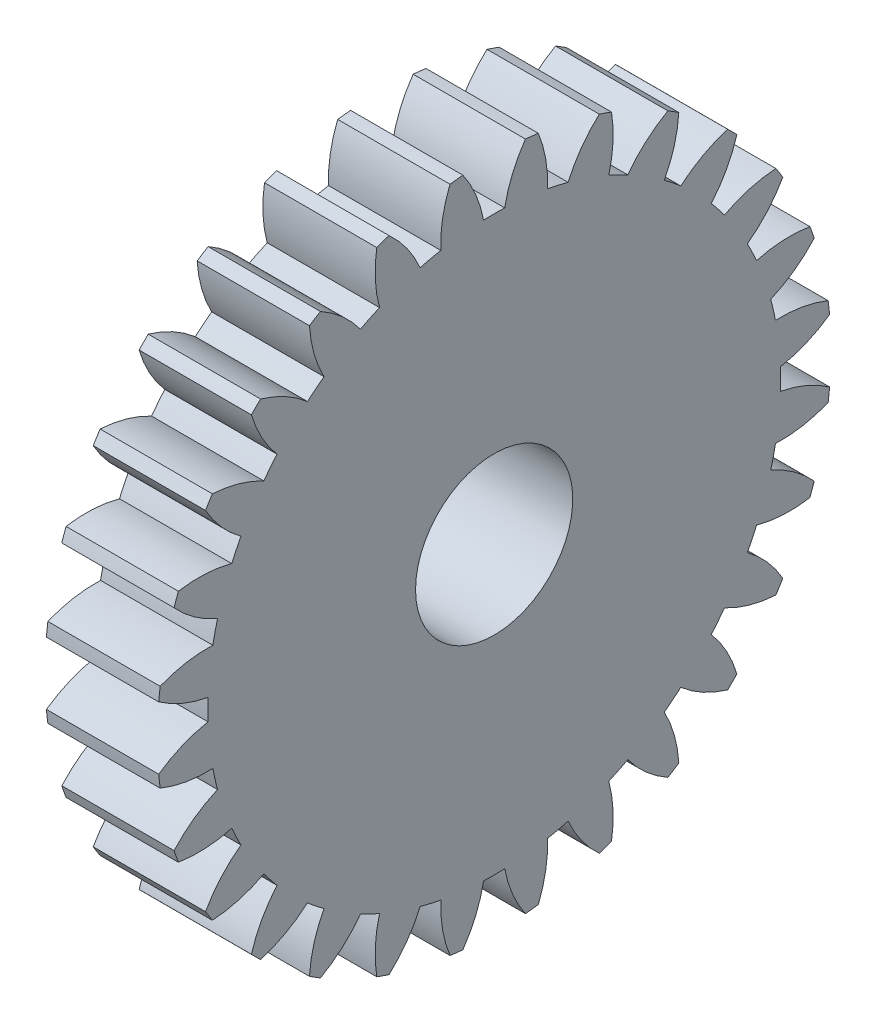
SolidWorks part; units mm, degrees
ref_plane "Plane1" through (0, 0, 0) normal (0, 0, 1) x (1, 0, 0)
ref_plane "Plane2" through (0, 0, 0) normal (0, 1, 0) x (1, 0, 0)
ref_plane "Plane3" through (0, 0, 0) normal (1, 0, 0) x (0, 0, -1)
sketch "HoldingSke" plane through (0, 0, 0) normal (0, 1, 0) x (1, 0, 0)
  line L0 (0, 0) -> (0.8829, -0.4695)
  line L1 (-15, 0) -> (100, 0) construction
  line L2 (0, 0) -> (-2.1039, 2.3779)
  line L3 (0, 0) -> (-11.863, 4.5341)
  line L4 (0, 0) -> (7.6251, 4.0544)
  line L5 (0, 0) -> (-46.8476, -17.4728)
  line L6 (0, 0) -> (-4.1448, -2.7965)
  line L7 (-2.1039, 2.3779) -> (8.6586, 51.2059)
  line L8 (-76.2, 54.61) -> (-75.2, 54.61)
  line L9 (-71.009, 38.7566) -> (-53.1078, 45.2721)
  line L10 (-76.2, 71.12) -> (104.1128, 71.12)
  line L11 (0, 0) -> (-5, 0)
  line L12 (-76.2, 101.6) -> (-76.162, 101.6)
  line L13 (24.9733, 27.94) -> (52.9518, 28.4284)
  line L14 (24.9733, 27.94) -> (24.9743, 27.94)
  line L15 (24.9733, 27.94) -> (100.4006, 29.5858)
  line L16 (-63.627, -1) -> (-12.827, -1)
  circle A0 centre (0, 0) radius 3.5
  circle A1 centre (0, 0) radius 12.749
  circle A2 centre (0, 0) radius 37.5
  circle A3 centre (0, 0) radius 3.5
  dimension "MHD" = 25.498
  dimension "Hub_dia" = 75
  dimension "Bore" = 7
  dimension "MBD" = 7
  dimension "Num_teeth" = 28
  dimension "Pitch" = 1
  dimension "Overall_len" = 50
  dimension "Show_teeth" = 28
  dimension "Thickness" = 5
  dimension "OAL" = 50.0001
  dimension "T_dim" = 1
  dimension "Ap" = 20
  dimension "H" = 19.05
  dimension "Pitch_radius" = 180.3128
  dimension "Width" = 5
  dimension "Backlash" = 0.038
  dimension "Addendum_fac" = 1
  dimension "Dedendum_fac" = 1.25
  dimension "Clearance_fac" = 0.25
  dimension "Dedendum_add" = 0.001
  dimension "Module" = 1
sketch "BasProSke" plane through (0, 0, 0) normal (0, 1, 0) x (1, 0, 0)
  line L0 (-10, 0) -> (60, 0) construction
  line L1 (0, 0) -> (0, 15)
  line L2 (0, 0) -> (5, 0)
  line L3 (5, 0) -> (5, 15)
  line L4 (5, 15) -> (0, 15)
  dimension "Thickness" = 5
  dimension "Diameter" = 30
revolve "Base-Revolve" add sketch "BasProSke" angle 360 about L0
sketch "TooCutSke" plane through (0, 0, 0) normal (1, 0, 0) x (0, 0, -1)
  line L1 (0, 0) -> (0, 107) construction
  line L2 (0, 0) -> (-0.8515, 13.9741) construction
  line L3 (0, 0) -> (-3.1309, 27.7873) construction
  line L4 (-0.8515, 13.9741) -> (-1.5654, 13.8936) construction
  arc A0 (0.4713, 12.7403) -> (-0.4713, 12.7403) centre (0, 0) ccw
  arc A1 (1.4098, 14.9591) -> (-1.4098, 14.9591) centre (0, 0) ccw
  circle A2 centre (0, 0) radius 14 construction
  circle A3 centre (0, 0) radius 13.1557 construction
  arc A4 (-0.4713, 12.7403) -> (-1.4098, 14.9591) centre (-5.9775, 11.7193) ccw
  arc A5 (1.4098, 14.9591) -> (0.4713, 12.7403) centre (5.9775, 11.7193) ccw
  dimension "Root_dia" = 25.498
  dimension "Overcut_dia" = 30.0508
  dimension "Pitch_dia" = 28
  dimension "Base_dia" = 26.3114
  dimension "Flank_rad" = 5.6
  dimension "Half_ang" = 6.429
  dimension "Half_CT" = 0.7185
extrude "ToothCut" cut sketch "TooCutSke" along normal through all
fillet "Breaks" [suppressed] radius 0.02
fillet "RootFillets" [suppressed] radius 0.251
pattern_circular "TeethCuts" count 28 every 12.857 about axis through (-10, 0, 0) along (1, 0, 0) of "ToothCut", "RootFillets", "Breaks"
sketch "HubNeaOneSke" plane through (0, 0, 0) normal (-1, 0, 0) x (0, 0, 1)
  circle A0 centre (0, 0) radius 12.749
  dimension "Diameter" = 25.498
extrude "HubNearOne" [suppressed] add sketch "HubNeaOneSke" along normal blind 45.0001
sketch "HubNeaBotSke" plane through (0, 0, 0) normal (-1, 0, 0) x (0, 0, 1)
  circle A0 centre (0, 0) radius 12.749
  dimension "Diameter" = 25.498
extrude "HubNearBoth" [suppressed] add sketch "HubNeaBotSke" along normal blind 22.5
ref_plane "FarPln" through (5, 0, 0) normal (1, 0, 0) x (0, 0, -1)
sketch "HubFarSke" plane through (5, 0, 0) normal (1, 0, 0) x (0, 0, -1)
  circle A0 centre (0, 0) radius 12.749
  dimension "Diameter" = 25.498
extrude "HubFar" [suppressed] add sketch "HubFarSke" along normal blind 22.5
sketch "BorSke" plane through (0, 0, 0) normal (1, 0, 0) x (0, 0, -1)
  circle A0 centre (0, 0) radius 3.5
  dimension "Diameter" = 7
extrude "Bore" cut sketch "BorSke" along normal mid plane 100.0001
sketch "KeySke" plane through (0, 0, 0) normal (1, 0, 0) x (0, 0, -1)
  line L0 (-1, 0) -> (-1, 4.5)
  line L1 (-1, 4.5) -> (1, 4.5)
  line L2 (1, 4.5) -> (1, 0)
  line L3 (0, 0) -> (0, 34) construction
  line L4 (-1, 0) -> (1, 0)
  dimension "Offset" = 4.5
  dimension "Width" = 2
extrude "Keyway" [suppressed] cut sketch "KeySke" along normal mid plane 100.0001
pattern_circular "Keyway2" [suppressed] count 2 every 90 about axis through (-10, 0, 0) along (1, 0, 0)
equation "' \"Module@HoldingSke\" = 6.35"
equation "' \"Num_teeth@HoldingSke\" = 12"
equation "' \"Ap@HoldingSke\" =  20"
equation "' \"Ap@HoldingSke\" = 20"
equation "' \"Width@HoldingSke\" = 0.5 * 25.4"
equation "' \"Hub_dia@HoldingSke\"= 1 * 25.4"
equation "' \"Hub_dia@HoldingSke\" = 1 * 25.4"
equation "' \"Overall_len@HoldingSke\" = 1.0 * 25.4"
equation "' \"Bore@HoldingSke\" = 0.75 * 25.4"
equation "' \"T_dim@HoldingSke\" = 0.1 * 25.4"
equation "' \"Width@KeySke\" = 0.25 * 25.4"
equation "' \"Show_teeth@HoldingSke\" = 13"
equation "' \"Backlash@HoldingSke\" = 0.009 * 25.4"
equation "' \"Addendum_fac@HoldingSke\" = 1.0"
equation "' \"Dedendum_fac@HoldingSke\" = 1.25"
equation "' \"Dedendum_add@HoldingSke\" = 0.00005 * 25.4"
equation "' \"Clearance_fac@HoldingSke\" = 0.25"
equation "\"Pitch@HoldingSke\" = 1 / \"Module@HoldingSke\""
equation "\"Overcut_dia@TooCutSke\" = (\"Num_teeth@HoldingSke\" + 2 * \"Addendum_fac@HoldingSke\") / \"Pitch@HoldingSke\" + 0.002 * 25.4"
equation "\"Pitch_dia@TooCutSke\" = \"Num_teeth@HoldingSke\" / \"Pitch@HoldingSke\""
equation "\"Base_dia@TooCutSke\" = \"Num_teeth@HoldingSke\" / \"Pitch@HoldingSke\" * cos((\"Ap@HoldingSke\"  * 3.14159265 / 180))"
equation "\"Root_dia@TooCutSke\" = (\"Num_teeth@HoldingSke\" + 2) / \"Pitch@HoldingSke\" - 2 * (\"Addendum_fac@HoldingSke\" + \"Dedendum_fac@HoldingSke\") / \"Pitch@HoldingSke\" - \"Dedendum_add@HoldingSke\" * 2"
equation "\"Half_ang@TooCutSke\" = 180 / \"Num_teeth@HoldingSke\""
equation "\"Half_CT@TooCutSke\" = \"Num_teeth@HoldingSke\" / \"Pitch@HoldingSke\" * sin((3.14159265 / 2 / \"Num_teeth@HoldingSke\")) / 2 - 7 * \"Backlash@HoldingSke\" / 4"
equation "\"Flank_rad@TooCutSke\" = \"Num_teeth@HoldingSke\" / \"Pitch@HoldingSke\" / 5"
equation "\"Radius@RootFillets\" = \"Clearance_fac@HoldingSke\" / \"Pitch@HoldingSke\" + \"Dedendum_add@HoldingSke\""
equation "\"Break_rad@Breaks\" = 0.02 / \"Pitch@HoldingSke\""
equation "\"Thickness@HoldingSke\" = \"Width@HoldingSke\""
equation "\"OAL@HoldingSke\" = \"Thickness@HoldingSke\""
equation "\"MHD@HoldingSke\" = (\"Num_teeth@HoldingSke\" + 2) / \"Pitch@HoldingSke\" - 2 * (\"Addendum_fac@HoldingSke\" + \"Dedendum_fac@HoldingSke\")  / \"Pitch@HoldingSke\" - \"Dedendum_add@HoldingSke\" * 2"
equation "\"MBD@HoldingSke\" = (\"Num_teeth@HoldingSke\" + 2) / \"Pitch@HoldingSke\" - 2 * (\"Addendum_fac@HoldingSke\" + \"Dedendum_fac@HoldingSke\")  / \"Pitch@HoldingSke\" - \"Dedendum_add@HoldingSke\" * 2 - 0.002 * 25.4"
equation "\"MHD@HoldingSke\" = ((sgn( \"MHD@HoldingSke\" - \"Hub_dia@HoldingSke\" )-1)*( \"MHD@HoldingSke\" - \"Hub_dia@HoldingSke\" ))/-2+ \"Hub_dia@HoldingSke\""
equation "\"MBD@HoldingSke\" = ((sgn( \"MBD@HoldingSke\" - \"Bore@HoldingSke\" )-1)*( \"MBD@HoldingSke\" - \"Bore@HoldingSke\" ))/-2+ \"Bore@HoldingSke\""
equation "\"OAL@HoldingSke\" = ((sgn( \"OAL@HoldingSke\" - \"Overall_len@HoldingSke\" )+1)*( \"OAL@HoldingSke\" - \"Overall_len@HoldingSke\" ))/2 + \"Overall_len@HoldingSke\" + 0.000002 * 25.4"
equation "\"Num_teeth@TeethCuts\" = int( \"Show_teeth@HoldingSke\" ) + 1"
equation "\"Num_teeth@TeethCuts\" = ((sgn( \"Num_teeth@TeethCuts\" - \"Num_teeth@HoldingSke\" )-1)*( \"Num_teeth@TeethCuts\" - \"Num_teeth@HoldingSke\" ))/-2+ \"Num_teeth@HoldingSke\""
equation "\"Num_teeth@TeethCuts\" = ((sgn( \"Num_teeth@TeethCuts\" - 2.0)+1)*( \"Num_teeth@TeethCuts\" - 2.0))/2 +2.0"
equation "\"Angle@TeethCuts\" = 360.0 / \"Num_teeth@HoldingSke\""
equation "\"Diameter@BasProSke\" = (\"Num_teeth@HoldingSke\" + 2 * \"Addendum_fac@HoldingSke\") / \"Pitch@HoldingSke\""
equation "\"Thickness@BasProSke\"  = \"Thickness@HoldingSke\""
equation "' \"Fillet_rad@BasProSke\" =  \"Thickness@HoldingSke\" * 0.05"
equation "' \"Fillet_rad@BasProSke\" = \"Thickness@HoldingSke\" * 0.05"
equation "\"MHD@HoldingSke\" = ((sgn( \"MHD@HoldingSke\" - \"Root_dia@TooCutSke\" )-1)*( \"MHD@HoldingSke\" - \"Root_dia@TooCutSke\" ))/-2+ \"Root_dia@TooCutSke\""
equation "\"Diameter@HubNeaOneSke\" = \"MHD@HoldingSke\""
equation "\"Length@HubNearOne\" = \"OAL@HoldingSke\" - \"Thickness@BasProSke\""
equation "\"Diameter@HubNeaBotSke\" = \"MHD@HoldingSke\""
equation "\"Length@HubNearBoth\" = ( \"OAL@HoldingSke\" - \"Thickness@BasProSke\" ) / 2.0"
equation "\"Thickness@FarPln\" = \"Thickness@BasProSke\""
equation "\"Diameter@HubFarSke\" = \"MHD@HoldingSke\""
equation "\"Length@HubFar\" = ( \"OAL@HoldingSke\" - \"Thickness@BasProSke\" ) / 2.0"
equation "\"Diameter@BorSke\" = \"MBD@HoldingSke\""
equation "\"D1@Bore\" = \"OAL@HoldingSke\" * 2.0"
equation "\"D1@Keyway\" = \"OAL@HoldingSke\" * 2.0"
equation "\"Offset@KeySke\" = \"T_dim@HoldingSke\" + \"MBD@HoldingSke\" / 2.0"
